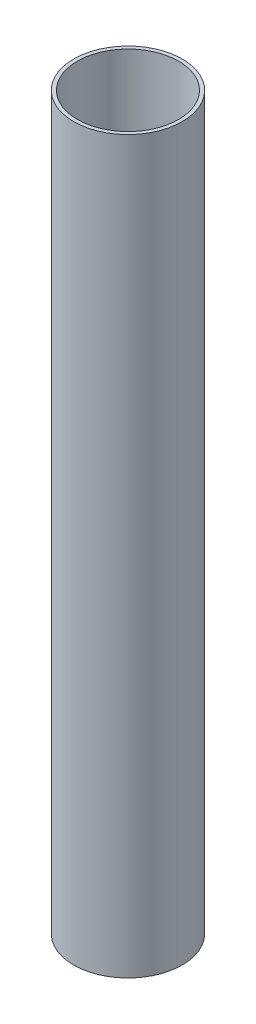
SolidWorks part; units mm, degrees
ref_plane "Front Plane" through (0, 0, 0) normal (0, 0, 1) x (1, 0, 0)
ref_plane "Top Plane" through (0, 0, 0) normal (0, 1, 0) x (1, 0, 0)
ref_plane "Right Plane" through (0, 0, 0) normal (1, 0, 0) x (0, 0, -1)
sketch "Sketch1" plane through (0, 0, 0) normal (0, 1, 0) x (1, 0, 0)
  circle A0 centre (0, 0) radius 20.7518
  circle A1 centre (0, 0) radius 19.3548
  dimension "D1" = 41.5036
  dimension "D2" = 38.7096
extrude "Boss-Extrude1" add sketch "Sketch1" along normal blind 279.4
